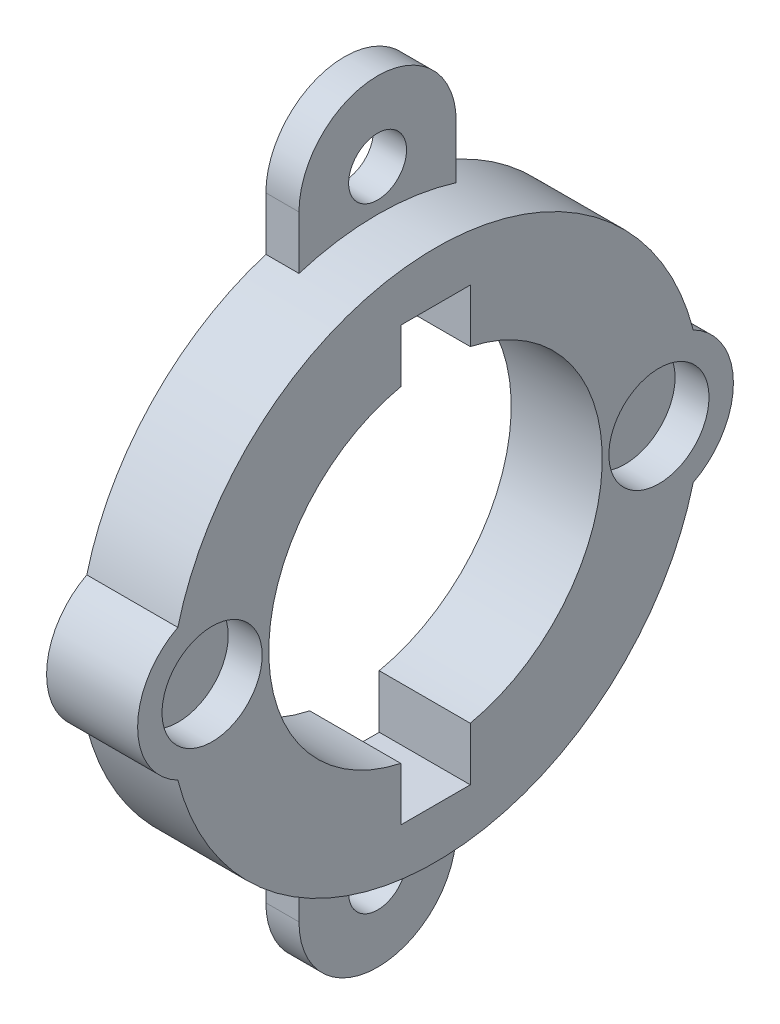
SolidWorks part; units mm, degrees
ref_plane "Front Plane" through (0, 0, 0) normal (0, 0, 1) x (1, 0, 0)
ref_plane "Top Plane" through (0, 0, 0) normal (0, 1, 0) x (1, 0, 0)
ref_plane "Right Plane" through (0, 0, 0) normal (1, 0, 0) x (0, 0, -1)
sketch "Sketch1" plane through (0, 0, 0) normal (1, 0, 0) x (0, 0, -1)
  line L0 (0, 18.575) -> (0, -18.575) construction
  line L1 (0, 0) -> (-16.075, 0) construction
  line L2 (0, 10.075) -> (0, 18.575) construction
  line L5 (0, 0) -> (16.075, 0) construction
  line L6 (4.75, 15.3572) -> (4.75, 18.575)
  line L7 (-4.75, 15.3572) -> (-4.75, 18.575)
  line L8 (4.75, -15.3572) -> (4.75, -18.575)
  line L10 (-4.75, -15.3572) -> (-4.75, -18.575)
  circle A0 centre (0, 18.575) radius 1.75
  circle A2 centre (0, 0) radius 10.075
  arc A3 (-4.75, 15.3572) -> (-4.75, -15.3572) centre (0, 0) ccw
  arc A4 (4.75, 18.575) -> (-4.75, 18.575) centre (0, 18.575) ccw
  arc A5 (4.75, -18.575) -> (-4.75, -18.575) centre (0, -18.575) cw
  circle A6 centre (0, -18.575) radius 1.75
  arc A7 (4.75, -15.3572) -> (4.75, 15.3572) centre (0, 0) ccw
  point P4 (0, 0)
  dimension "D1" = 3.5
  dimension "D2" = 20.15
  dimension "D3" = 6
  dimension "D6" = 3
  dimension "D4" = 90
  dimension "D5" = 8.5
extrude "Boss-Extrude1" add sketch "Sketch1" along normal blind 5
sketch "Sketch2" plane through (0, 0, 0) normal (-1, 0, 0) x (0, 0, 1)
  line L0 (0, 10.075) -> (0, 13.075) construction
  line L1 (-2.1, 13.075) -> (2.1, 13.075)
  line L2 (-2.1, 13.075) -> (-2.1, -13.075)
  line L3 (-2.1, -13.075) -> (2.1, -13.075)
  line L4 (2.1, 13.075) -> (2.1, -13.075)
  circle A0 centre (0, 0) radius 10.075 construction
  point P4 (0, 13.075)
  point P6 (2.1, 0)
  dimension "D1" = 4.2
  dimension "D2" = 3
extrude "Cut-Extrude1" cut sketch "Sketch2" against normal up to next
sketch "Sketch3" plane through (5, 0, 0) normal (1, 0, 0) x (0, 0, -1)
  line L6 (-2.1, 13.075) -> (-2.1, 9.8537)
  line L7 (2.1, 13.075) -> (-2.1, 13.075)
  line L8 (2.1, 9.8537) -> (2.1, 13.075)
  line L9 (2.1, -13.075) -> (2.1, -9.8537)
  line L10 (-2.1, -13.075) -> (2.1, -13.075)
  line L11 (-2.1, -9.8537) -> (-2.1, -13.075)
  line L12 (-2.1, 13.075) -> (-2.1, 9.8537)
  line L13 (2.1, 13.075) -> (-2.1, 13.075)
  line L14 (2.1, 9.8537) -> (2.1, 13.075)
  line L15 (2.1, -13.075) -> (2.1, -9.8537)
  line L16 (-2.1, -13.075) -> (2.1, -13.075)
  line L17 (-2.1, -9.8537) -> (-2.1, -13.075)
  circle A0 centre (0, 0) radius 16.075
  arc A1 (4.75, -15.3572) -> (4.75, 15.3572) centre (0, 0) ccw construction
  arc A4 (2.1, -9.8537) -> (2.1, 9.8537) centre (0, 0) ccw
  arc A5 (-2.1, 9.8537) -> (-2.1, -9.8537) centre (0, 0) ccw
  arc A6 (2.1, -9.8537) -> (2.1, 9.8537) centre (0, 0) ccw
  arc A7 (-2.1, 9.8537) -> (-2.1, -9.8537) centre (0, 0) ccw
  dimension "D1" = 0
extrude "Boss-Extrude2" add sketch "Sketch3" along normal blind 0.5
sketch "Sketch4" plane through (0, 0, 0) normal (-1, 0, 0) x (0, 0, 1)
  line L2 (0, -1000) -> (0, 49000) construction
  line L5 (-13.5, -4.5) -> (-9.0142, -4.5)
  line L6 (-13.5, 4.5) -> (-9.0142, 4.5)
  line L7 (13.5, 4.5) -> (9.0142, 4.5)
  line L8 (13.5, -4.5) -> (9.0142, -4.5)
  circle A0 centre (-13.5, 0) radius 2.5 construction
  arc A1 (-13.5, 4.5) -> (-13.5, -4.5) centre (-13.5, 0) ccw
  arc A2 (-4.75, 15.3572) -> (-4.75, -15.3572) centre (0, 0) ccw construction
  arc A7 (-2.1, 9.8537) -> (-2.1, -9.8537) centre (0, 0) ccw construction
  arc A8 (-9.0142, 4.5) -> (-9.0142, -4.5) centre (0, 0) ccw
  circle A9 centre (13.5, 0) radius 2.5 construction
  arc A10 (9.0142, 4.5) -> (9.0142, -4.5) centre (0, 0) cw
  arc A11 (13.5, 4.5) -> (13.5, -4.5) centre (13.5, 0) cw
  dimension "D2" = 5
  dimension "D3" = 2
  dimension "D1" = 13.5
extrude "Boss-Extrude3" add sketch "Sketch4" against normal up to surface (5.5 mm away) up to face at (5.5, 0, -16.075)
sketch "Sketch5" plane through (5.5, 0, 0) normal (1, 0, 0) x (0, 0, -1)
  line L0 (-18, 0) -> (-17.0625, 0) construction
  line L1 (-17.0625, 0) -> (-11.0125, 0) construction
  line L2 (9.0142, -4.5) -> (13.5, -4.5)
  line L3 (13.5, 4.5) -> (9.0142, 4.5)
  line L4 (9.0142, -4.5) -> (13.5, -4.5) construction
  line L5 (13.5, 4.5) -> (9.0142, 4.5) construction
  line L9 (-9.0142, 4.5) -> (-13.5, 4.5)
  line L12 (-13.5, -4.5) -> (-9.0142, -4.5)
  line L13 (-9.0142, 4.5) -> (-13.5, 4.5) construction
  line L14 (-13.5, -4.5) -> (-9.0142, -4.5) construction
  line L15 (-11.0125, 0) -> (-10.075, 0) construction
  line L16 (0, -13.075) -> (0, 13.075) construction
  line L17 (-2.1, -13.075) -> (2.1, -13.075) construction
  line L18 (2.1, 13.075) -> (-2.1, 13.075) construction
  circle A0 centre (-13.5, 0) radius 3.025
  circle A1 centre (13.5, 0) radius 3.025
  circle A2 centre (-14.0375, 0) radius 3.025 construction
  circle A3 centre (14.0375, 0) radius 3.025 construction
  arc A14 (9.0142, -4.5) -> (9.0142, 4.5) centre (0, 0) ccw
  arc A15 (13.5, -4.5) -> (13.5, 4.5) centre (13.5, 0) ccw
  arc A21 (9.0142, -4.5) -> (9.0142, 4.5) centre (0, 0) ccw construction
  arc A22 (13.5, -4.5) -> (13.5, 4.5) centre (13.5, 0) ccw construction
  arc A23 (-9.0142, 4.5) -> (-9.0142, -4.5) centre (0, 0) ccw
  arc A24 (-13.5, 4.5) -> (-13.5, -4.5) centre (-13.5, 0) ccw
  arc A25 (-9.0142, 4.5) -> (-9.0142, -4.5) centre (0, 0) ccw construction
  arc A26 (-13.5, 4.5) -> (-13.5, -4.5) centre (-13.5, 0) ccw construction
  dimension "D3" = 6.05
  dimension "D1" = 0
  dimension "D2" = 0
extrude "Cut-Extrude2" cut sketch "Sketch5" against normal blind 2.05
sketch "Sketch6" plane through (5, 0, 0) normal (1, 0, 0) x (0, 0, -1)
  line L2 (4.75, 15.3572) -> (4.75, 18.575)
  line L3 (-4.75, 18.575) -> (-4.75, 15.3572)
  line L4 (4.75, 15.3572) -> (4.75, 18.575)
  line L5 (-4.75, 18.575) -> (-4.75, 15.3572)
  line L6 (-4.75, -15.3572) -> (-4.75, -18.575)
  line L7 (4.75, -18.575) -> (4.75, -15.3572)
  line L8 (-4.75, -15.3572) -> (-4.75, -18.575)
  line L9 (4.75, -18.575) -> (4.75, -15.3572)
  arc A2 (4.75, 15.3572) -> (-4.75, 15.3572) centre (0, 0) ccw
  arc A3 (4.75, 18.575) -> (-4.75, 18.575) centre (0, 18.575) ccw
  arc A4 (4.75, 15.3572) -> (-4.75, 15.3572) centre (0, 0) ccw
  arc A5 (4.75, 18.575) -> (-4.75, 18.575) centre (0, 18.575) ccw
  arc A6 (-4.75, -15.3572) -> (4.75, -15.3572) centre (0, 0) ccw
  arc A7 (-4.75, -18.575) -> (4.75, -18.575) centre (0, -18.575) ccw
  arc A8 (-4.75, -15.3572) -> (4.75, -15.3572) centre (0, 0) ccw
  arc A9 (-4.75, -18.575) -> (4.75, -18.575) centre (0, -18.575) ccw
  dimension "D1" = 0
  dimension "D2" = 0
extrude "Cut-Extrude3" cut sketch "Sketch6" against normal offset from surface (3 mm away) 2 up to face at (0, 0, 0)
